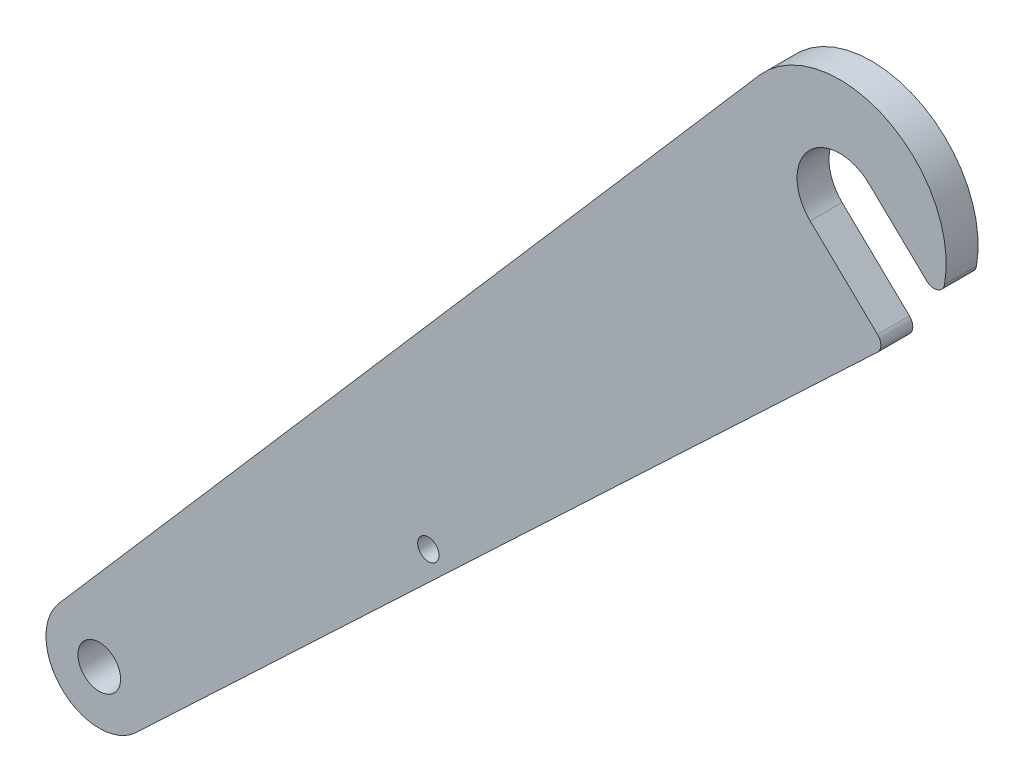
SolidWorks part; units mm, degrees
material "Thornel Mat VMA"
ref_plane "前视基准面" through (0, 0, 0) normal (0, 0, 1) x (1, 0, 0)
ref_plane "上视基准面" through (0, 0, 0) normal (0, 1, 0) x (1, 0, 0)
ref_plane "右视基准面" through (0, 0, 0) normal (1, 0, 0) x (0, 0, -1)
sketch "草图1" plane through (0, 0, 0) normal (0, 0, 1) x (1, 0, 0)
  line L0 (0, 0) -> (69.5, 72.5) construction
  line L1 (66.7319, 69.6125) -> (73.8158, 62.8217)
  line L2 (72.2681, 75.3875) -> (78.8842, 69.0451)
  line L3 (-3.7772, 3.2761) -> (61.9456, 79.0522)
  line L4 (73.8158, 62.8217) -> (3.4327, -3.6355)
  circle A0 centre (0, 0) radius 2
  arc A1 (72.2681, 75.3875) -> (66.7319, 69.6125) centre (69.5, 72.5) ccw
  arc A2 (-3.7772, 3.2761) -> (3.4327, -3.6355) centre (0, 0) ccw
  arc A3 (61.9456, 79.0522) -> (78.8842, 69.0451) centre (69.5, 72.5) cw
  circle A4 centre (30.8918, 25) radius 1
  dimension "D3" = 4
  dimension "D4" = 8
  dimension "D5" = 10
  dimension "D6" = 10
  dimension "D7" = 5
  dimension "D8" = 25
  dimension "D9" = 2
  dimension "D1" = 72.5
  dimension "D2" = 69.5
extrude "凸台-拉伸1" add sketch "草图1" along normal blind 3
fillet "圆角1" radius 1 2 edges at (78.8842, 69.0451, 1.5) (73.8158, 62.8217, 1.5)
